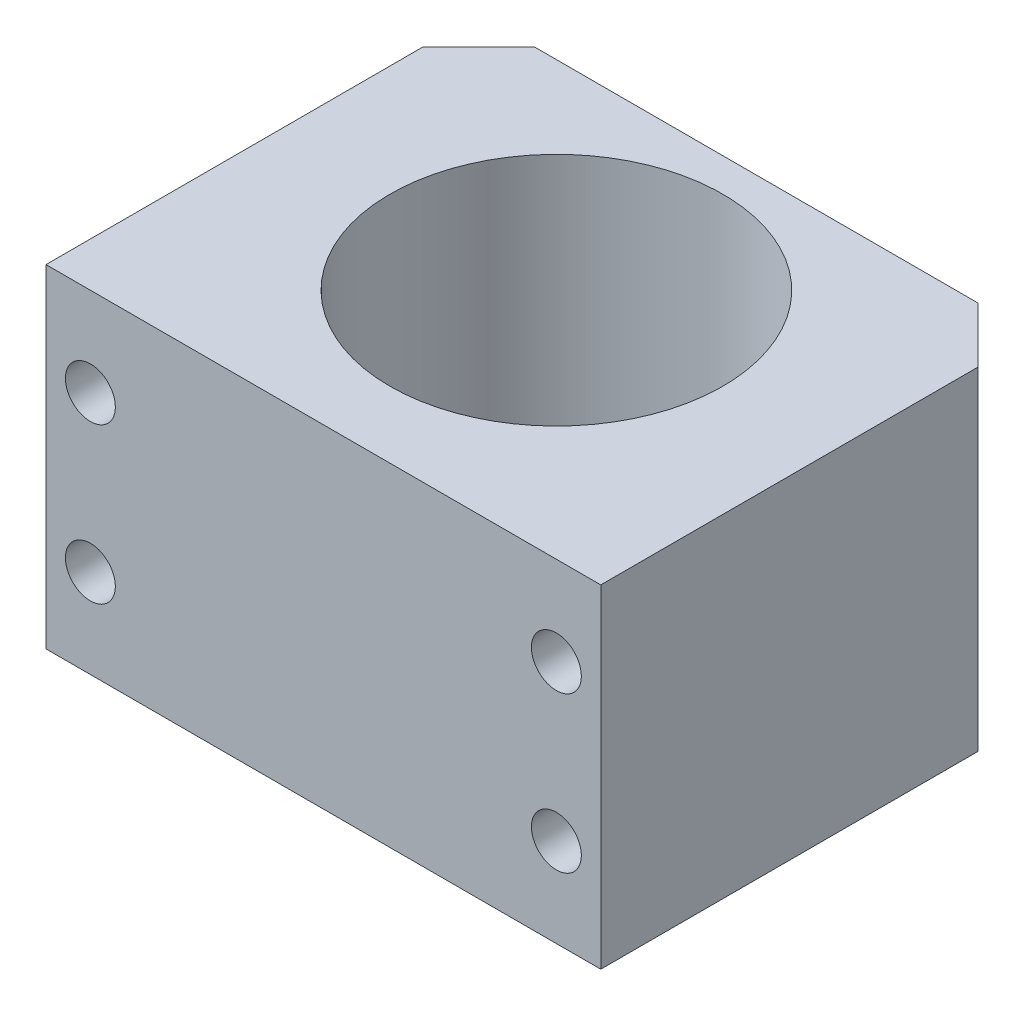
SolidWorks part; units mm, degrees
ref_plane "정면" through (0, 0, 0) normal (0, 0, 1) x (1, 0, 0)
ref_plane "윗면" through (0, 0, 0) normal (0, 1, 0) x (1, 0, 0)
ref_plane "우측면" through (0, 0, 0) normal (1, 0, 0) x (0, 0, -1)
sketch "스케치1" plane through (0, 0, 0) normal (0, 1, 0) x (1, 0, 0)
  line L1 (-25, -19.5) -> (25, -19.5)
  line L2 (-25, -19.5) -> (-25, 19.5)
  line L3 (-25, 19.5) -> (25, 19.5)
  line L4 (25, -19.5) -> (25, 19.5)
  line L5 (-25, -19.5) -> (25, 19.5) construction
  line L6 (-25, 19.5) -> (25, -19.5) construction
  point P0 (0, 0)
  dimension "D1" = 39
  dimension "D2" = 50
extrude "보스-돌출1" add sketch "스케치1" along normal blind 30
sketch "스케치2" plane through (0, 30, 0) normal (0, 1, 0) x (1, 0, 0)
  line L0 (-25, -19.5) -> (25, -19.5) construction
  circle A0 centre (0, 1.5) radius 15
  dimension "D1" = 30
  dimension "D2" = 21
extrude "컷-돌출1" cut sketch "스케치2" against normal blind 30
chamfer "모따기1" distance 5 angle 45 2 edges at (25, 15, -19.5) (-25, 15, -19.5)
hole_wizard "M4 여유 구멍1" positions "스케치4" profile "스케치3" hole size "M4" standard "Ansi Metric"
sketch "스케치4" plane through (0, 0, 19.5) normal (0, 0, 1) x (1, 0, 0)
  line L1 (-21, 22) -> (21, 22) construction
  line L2 (-21, 22) -> (-21, 8) construction
  line L3 (-21, 8) -> (21, 8) construction
  line L4 (21, 22) -> (21, 8) construction
  line L5 (25, 30) -> (25, 0) construction
  line L6 (-25, 30) -> (-25, 0) construction
  line L7 (-25, 30) -> (25, 30) construction
  line L8 (-25, 0) -> (25, 0) construction
  point P0 (-21, 22)
  point P2 (21, 22)
  point P4 (21, 8)
  point P6 (-21, 8)
  dimension "D1" = 4
  dimension "D2" = 4
  dimension "D3" = 8
  dimension "D4" = 8
  dimension "D5" = 14
  dimension "D6" = 42
sketch "스케치3" plane through (-21, 22, 19.5) normal (1, 0, 0) x (0, -1, 0)
  line L0 (0, 0) -> (0, 21.3519)
  line L1 (0, 21.3519) -> (2.25, 20)
  line L2 (2.25, 20) -> (2.25, 0)
  line L5 (2.25, 0) -> (0, 0)
  line L10 (0, 21.3519) -> (-2.25, 20) construction
  line L11 (0, -6.35) -> (0, 107.95) construction
  dimension "구멍 지름" = 4.5
  dimension "구멍 깊이" = 20
  dimension "드릴 각도" = 118
